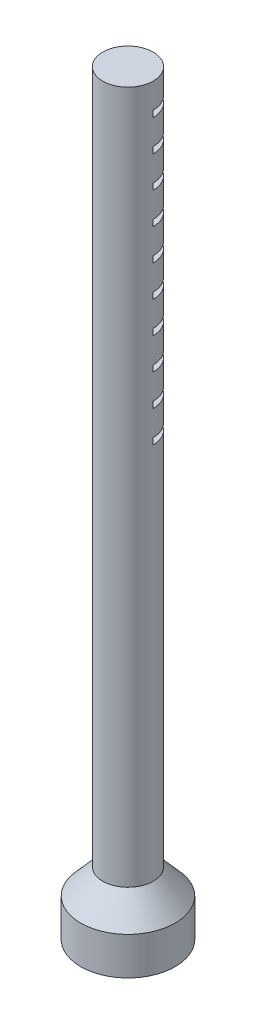
SolidWorks part; units mm, degrees
material "Nailon 6/10"
ref_plane "Alzado" through (0, 0, 0) normal (0, 0, 1) x (1, 0, 0)
ref_plane "Planta" through (0, 0, 0) normal (0, 1, 0) x (1, 0, 0)
ref_plane "Vista lateral" through (0, 0, 0) normal (1, 0, 0) x (0, 0, -1)
sketch "Croquis2" plane through (0, 0, 0) normal (0, 0, 1) x (1, 0, 0)
  line L0 (0, 34.0835) -> (0, -38.0933) construction
  line L1 (0, -14.7472) -> (3.75, -14.7472)
  line L2 (3.75, -14.7472) -> (3.75, -11.7472)
  line L3 (3.75, -11.7472) -> (2, -9.7472)
  line L4 (2, -9.7472) -> (2, 45.2528)
  line L5 (2, 45.2528) -> (0, 45.2528)
  line L6 (0, 45.2528) -> (0, -14.7472)
  dimension "D1" = 3.75
  dimension "D2" = 2
  dimension "D3" = 60
  dimension "D4" = 3
  dimension "D5" = 2
revolve "Revolución1" add sketch "Croquis2" angle 360 about L0
sketch "Croquis3" plane through (0, 0, 0) normal (0, 0, 1) x (1, 0, 0)
  line L0 (2, 45.2528) -> (2, 43.2528)
  line L1 (2, -9.7472) -> (2, 45.2528) construction
  line L2 (2, 43.2528) -> (1.0157, 43.2528)
  line L3 (1.0157, 43.2528) -> (1.0157, 42.7528)
  line L4 (1.0157, 42.7528) -> (2, 42.7528)
  line L5 (2, 42.7528) -> (2, 40.7528)
  line L6 (2, 40.7528) -> (1.0157, 40.7528)
  line L7 (1.0157, 40.7528) -> (1.0157, 40.2528)
  line L8 (1.0157, 40.2528) -> (2, 40.2528)
  line L9 (2, 40.2528) -> (2, 38.2528)
  line L10 (2, 38.2528) -> (1.0157, 38.2528)
  line L11 (1.0157, 38.2528) -> (1.0157, 37.7528)
  line L12 (1.0157, 37.7528) -> (2, 37.7528)
  line L13 (2, 37.7528) -> (2, 35.7528)
  line L14 (2, 35.7528) -> (1.0157, 35.7528)
  line L15 (1.0157, 35.7528) -> (1.0157, 35.2528)
  line L16 (1.0157, 35.2528) -> (2, 35.2528)
  line L17 (2, 35.2528) -> (2, 33.2528)
  line L18 (2, 33.2528) -> (1.0157, 33.2528)
  line L19 (1.0157, 33.2528) -> (1.0157, 32.7528)
  line L20 (1.0157, 32.7528) -> (2, 32.7528)
  line L21 (2, 32.7528) -> (2, 30.7528)
  line L22 (2, 30.7528) -> (1.0157, 30.7528)
  line L23 (1.0157, 30.7528) -> (1.0157, 30.2528)
  line L24 (1.0157, 30.2528) -> (2, 30.2528)
  line L25 (2, 30.2528) -> (2, 28.2528)
  line L26 (2, 28.2528) -> (1.0157, 28.2528)
  line L27 (1.0157, 28.2528) -> (1.0157, 27.7528)
  line L28 (1.0157, 27.7528) -> (2, 27.7528)
  line L29 (2, 27.7528) -> (2, 25.7528)
  line L30 (2, 25.7528) -> (1.0157, 25.7528)
  line L31 (1.0157, 25.7528) -> (1.0157, 25.2528)
  line L32 (1.0157, 25.2528) -> (2, 25.2528)
  line L33 (2, 25.2528) -> (2, 23.2528)
  line L34 (2, 23.2528) -> (1.0157, 23.2528)
  line L35 (1.0157, 23.2528) -> (1.0157, 22.7528)
  line L36 (1.0157, 22.7528) -> (2, 22.7528)
  line L37 (2, 22.7528) -> (2, 20.7528)
  line L38 (2, 20.7528) -> (1.0157, 20.7528)
  line L39 (1.0157, 20.7528) -> (1.0157, 20.2528)
  line L40 (1.0157, 20.2528) -> (2, 20.2528)
  line L41 (2, 20.2528) -> (3.9349, 20.2528)
  line L42 (3.9349, 20.2528) -> (3.9349, 45.2528)
  line L43 (3.9349, 45.2528) -> (2, 45.2528)
  dimension "D1" = 0.5
  dimension "D2" = 2
  dimension "D3" = 10
extrude "Cortar-Extruir1" cut sketch "Croquis3" against normal through all
